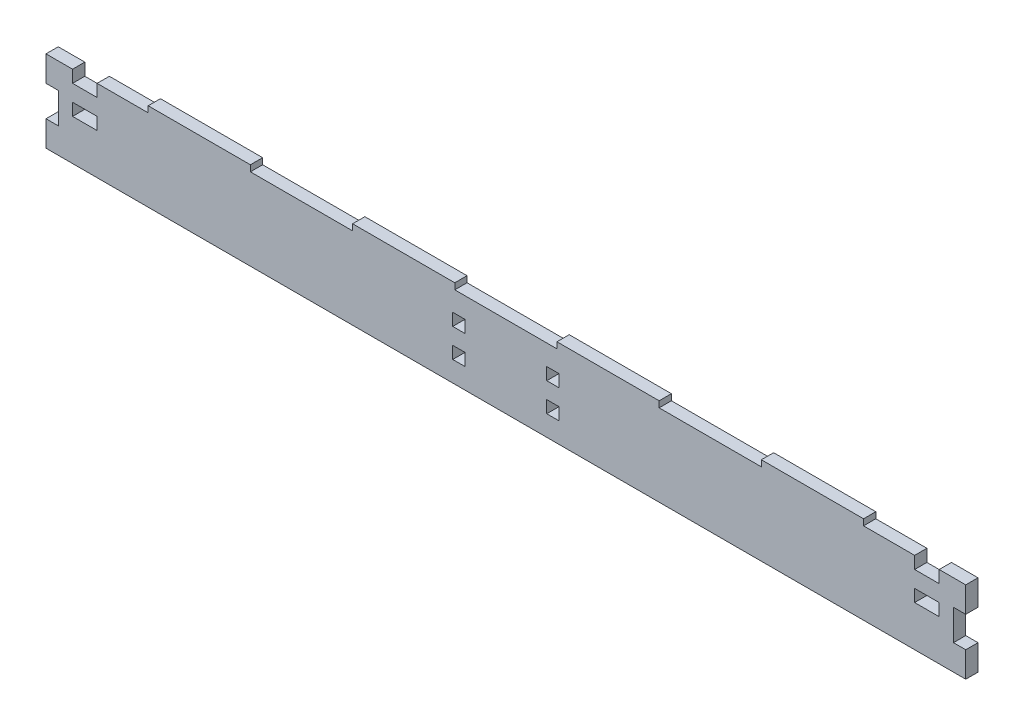
SolidWorks part; units mm, degrees
ref_plane "Спереди" through (0, 0, 0) normal (0, 0, 1) x (1, 0, 0)
ref_plane "Сверху" through (0, 0, 0) normal (0, 1, 0) x (1, 0, 0)
ref_plane "Справа" through (0, 0, 0) normal (1, 0, 0) x (0, 0, -1)
sketch "Эскиз1" plane through (0, 0, 0) normal (0, 0, 1) x (1, 0, 0)
  line L0 (100, 40) -> (150, 40)
  line L1 (0, 0) -> (450, 0)
  line L2 (0, 0) -> (0, 12.5)
  line L3 (0, 40) -> (13, 40)
  line L4 (450, 0) -> (450, 12.5)
  line L5 (0, 27.5) -> (6, 27.5)
  line L7 (0, 12.5) -> (6, 12.5)
  line L8 (6, 27.5) -> (6, 12.5)
  line L9 (450, 27.5) -> (444, 27.5)
  line L11 (450, 12.5) -> (444, 12.5)
  line L12 (444, 27.5) -> (444, 12.5)
  line L14 (50, 40) -> (50, 43)
  line L15 (50, 43) -> (100, 43)
  line L16 (100, 40) -> (100, 43)
  line L18 (150, 40) -> (150, 43)
  line L19 (150, 43) -> (200, 43)
  line L20 (200, 40) -> (200, 43)
  line L22 (250, 40) -> (250, 43)
  line L23 (250, 43) -> (300, 43)
  line L24 (300, 40) -> (300, 43)
  line L26 (350, 40) -> (350, 43)
  line L27 (350, 43) -> (400, 43)
  line L28 (400, 40) -> (400, 43)
  line L29 (200, 40) -> (250, 40)
  line L30 (300, 40) -> (350, 40)
  line L31 (400, 40) -> (425, 40)
  line L32 (0, 27.5) -> (0, 40)
  line L33 (450, 27.5) -> (450, 40)
  line L34 (25, 40) -> (50, 40)
  line L36 (13, 40) -> (13, 34)
  line L37 (13, 34) -> (25, 34)
  line L38 (25, 40) -> (25, 34)
  line L39 (13, 26) -> (25, 26)
  line L40 (13, 26) -> (13, 20)
  line L41 (13, 20) -> (25, 20)
  line L42 (25, 26) -> (25, 20)
  line L43 (437, 40) -> (450, 40)
  line L45 (437, 40) -> (437, 34)
  line L46 (437, 34) -> (425, 34)
  line L47 (425, 40) -> (425, 34)
  line L48 (437, 26) -> (425, 26)
  line L49 (437, 26) -> (437, 20)
  line L50 (437, 20) -> (425, 20)
  line L51 (425, 26) -> (425, 20)
  line L53 (245, 10) -> (205, 10) construction
  line L54 (251, 30) -> (245, 30)
  line L55 (251, 30) -> (251, 24)
  line L56 (251, 24) -> (245, 24)
  line L57 (245, 30) -> (245, 24)
  line L58 (251, 16) -> (245, 16)
  line L59 (251, 16) -> (251, 10)
  line L60 (251, 10) -> (245, 10)
  line L61 (245, 16) -> (245, 10)
  line L62 (205, 30) -> (199, 30)
  line L63 (205, 30) -> (205, 24)
  line L64 (205, 24) -> (199, 24)
  line L65 (199, 30) -> (199, 24)
  line L66 (205, 16) -> (199, 16)
  line L67 (205, 16) -> (205, 10)
  line L68 (205, 10) -> (199, 10)
  line L69 (199, 16) -> (199, 10)
  point P45 (225, 0)
  point P63 (225, 10)
  dimension "D1" = 450
  dimension "D2" = 40
  dimension "D3" = 50
  dimension "D4" = 50
  dimension "D5" = 50
  dimension "D6" = 50
  dimension "D7" = 50
  dimension "D8" = 50
  dimension "D9" = 50
  dimension "D10" = 50
  dimension "D11" = 3
  dimension "D12" = 15
  dimension "D13" = 12.5
  dimension "D14" = 6
  dimension "D15" = 6
  dimension "D16" = 12
  dimension "D17" = 6
  dimension "D18" = 6
  dimension "D19" = 7
  dimension "D20" = 8
  dimension "D21" = 7
  dimension "D22" = 12
  dimension "D23" = 6
  dimension "D24" = 6
  dimension "D25" = 6
  dimension "D26" = 6
  dimension "D27" = 40
  dimension "D28" = 10
  dimension "D29" = 8
extrude "Бобышка-Вытянуть1" add sketch "Эскиз1" along normal blind 6
